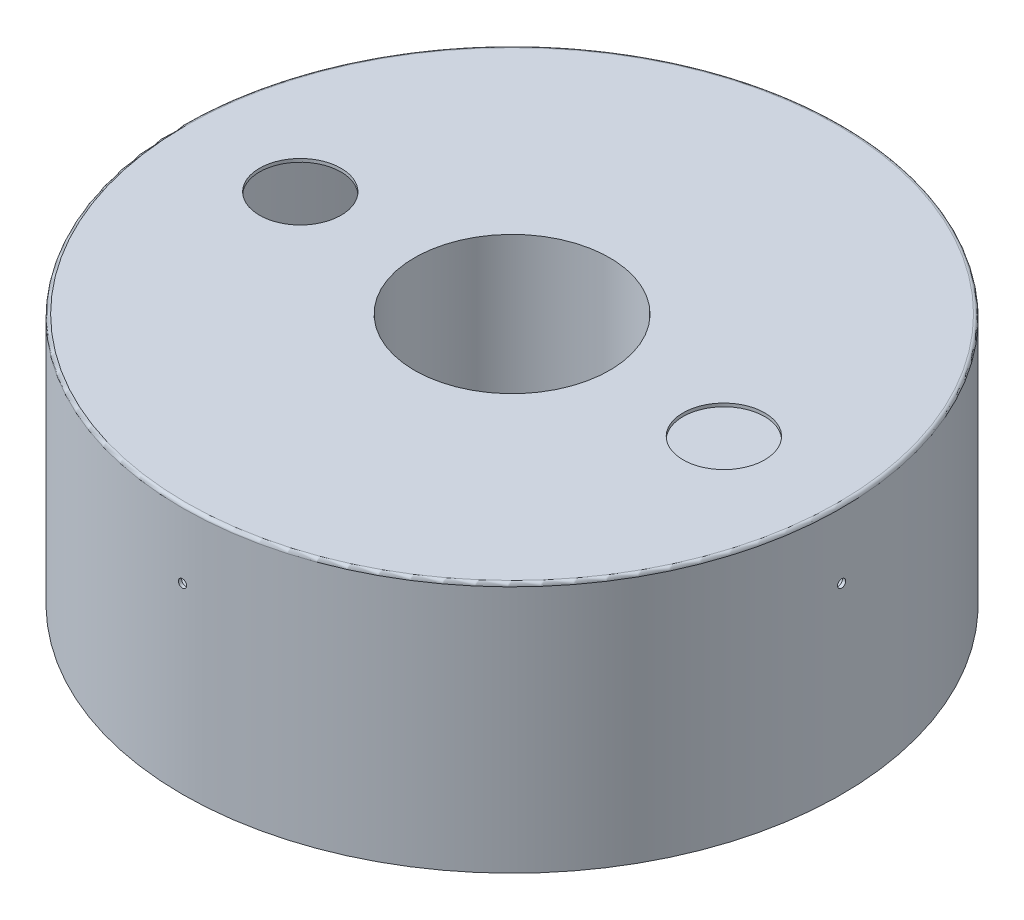
SolidWorks part; units mm, degrees
material "2014 Alloy"
ref_plane "Front Plane" through (0, 0, 0) normal (0, 0, 1) x (1, 0, 0)
ref_plane "Top Plane" through (0, 0, 0) normal (0, 1, 0) x (1, 0, 0)
ref_plane "Right Plane" through (0, 0, 0) normal (1, 0, 0) x (0, 0, -1)
sketch "Sketch9" plane through (0, 0, 0) normal (0, 1, 0) x (1, 0, 0)
  circle A0 centre (0, 0) radius 2000
extrude "Boss-Extrude5" add sketch "Sketch9" along normal blind 1500
sketch "Sketch10" plane through (0, 1500, 0) normal (0, 1, 0) x (1, 0, 0)
  circle A0 centre (0, 0) radius 598.217
extrude "Cut-Extrude3" cut sketch "Sketch10" against normal blind 1500
shell "Shell6" thickness 20
sketch "Sketch11" plane through (0, 1520, 0) normal (0, 1, 0) x (1, 0, 0)
  circle A0 centre (0, 0) radius 598.217
extrude "Boss-Extrude6" add sketch "Sketch11" against normal through all
sketch "Sketch13" plane through (0, 1520, 0) normal (0, 1, 0) x (1, 0, 0)
  circle A0 centre (0, 0) radius 618.217
extrude "Boss-Extrude7" add sketch "Sketch13" against normal through all
sketch "Sketch14" plane through (0, 1520, 0) normal (0, 1, 0) x (1, 0, 0)
  circle A0 centre (0, 0) radius 598.217
extrude "Cut-Extrude5" cut sketch "Sketch14" against normal through all
fillet "Fillet2" radius 20 1 edges at (0, 1520, 2020)
sketch "Sketch16" plane through (0, 1520, 0) normal (0, 1, 0) x (1, 0, 0)
  circle A0 centre (-1298.217, 0) radius 250
  circle A1 centre (1298.217, 0) radius 250
  dimension "D1" = 2
extrude "Cut-Extrude6" cut sketch "Sketch16" against normal blind 547 and the other way through all
sketch "Sketch19" plane through (0, 0, 0) normal (0, 0, 1) x (1, 0, 0)
  circle A0 centre (0, 1100) radius 24.963
extrude "Cut-Extrude11" cut sketch "Sketch19" along normal blind 300 and the other way blind 100 from offset 1800
pattern_circular "CirPattern1" count 4 every 90 about axis through (0, 1520, 0) along (0, 1, 0) of "Cut-Extrude11"
